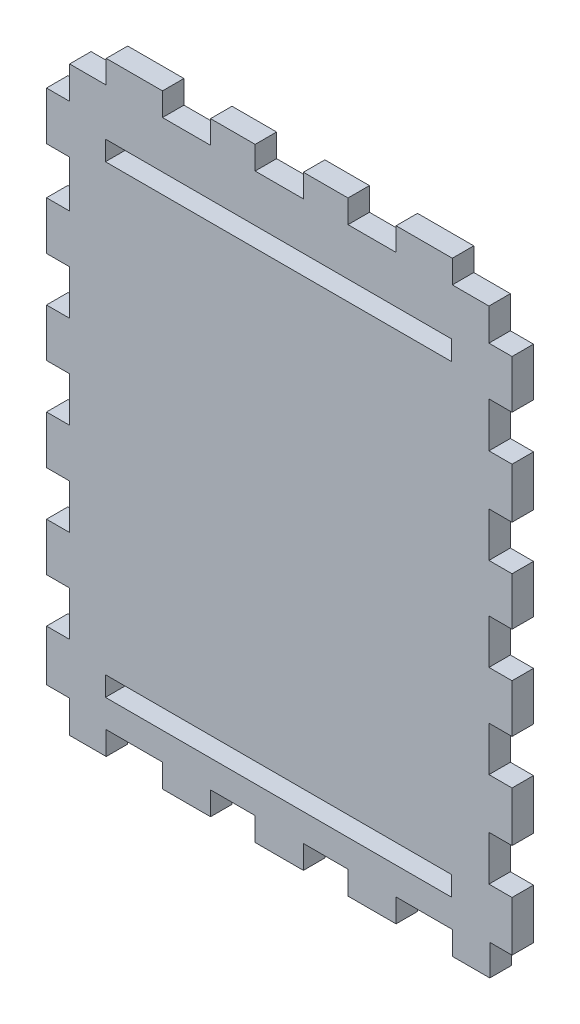
SolidWorks part; units mm, degrees
ref_plane "Front Plane" through (0, 0, 0) normal (0, 0, 1) x (1, 0, 0)
ref_plane "Top Plane" through (0, 0, 0) normal (0, 1, 0) x (1, 0, 0)
ref_plane "Right Plane" through (0, 0, 0) normal (1, 0, 0) x (0, 0, -1)
sketch "Model" plane through (0, 0, 0) normal (0, 0, 1) x (1, 0, 0)
  line L0 (167.6676, 180.7633) -> (171.654, 180.7633)
  line L1 (171.654, 180.7633) -> (171.654, 172.0927)
  line L2 (171.654, 172.0927) -> (167.6676, 172.0927)
  line L3 (167.6676, 172.0927) -> (167.6676, 164.4022)
  line L4 (167.6676, 164.4022) -> (171.654, 164.4022)
  line L5 (171.654, 164.4022) -> (171.654, 156.1119)
  line L6 (171.654, 156.1119) -> (167.6676, 156.1119)
  line L7 (167.6676, 156.1119) -> (167.6676, 153.3045)
  line L8 (95.3481, 202.3963) -> (101.6629, 202.3963)
  line L9 (101.6629, 202.3963) -> (101.6629, 206.3827)
  line L10 (101.6629, 206.3827) -> (111.3643, 206.3827)
  line L11 (111.3643, 206.3827) -> (111.3643, 202.3963)
  line L12 (111.3643, 202.3963) -> (119.6545, 202.3963)
  line L13 (119.6545, 202.3963) -> (119.6545, 206.3827)
  line L14 (119.6545, 206.3827) -> (127.3451, 206.3827)
  line L15 (127.3451, 206.3827) -> (127.3451, 202.3963)
  line L16 (127.3451, 202.3963) -> (135.6706, 202.3963)
  line L17 (135.6706, 202.3963) -> (135.6706, 206.3827)
  line L18 (135.6706, 206.3827) -> (143.3612, 206.3827)
  line L19 (143.3612, 206.3827) -> (143.3612, 202.3963)
  line L20 (143.3612, 202.3963) -> (151.6515, 202.3963)
  line L21 (151.6515, 202.3963) -> (151.6515, 206.3827)
  line L22 (151.6515, 206.3827) -> (161.3529, 206.3827)
  line L23 (161.3529, 206.3827) -> (161.3529, 202.3963)
  line L24 (161.3529, 202.3963) -> (167.6676, 202.3963)
  line L25 (95.3481, 124.1149) -> (91.3617, 124.1149)
  line L26 (91.3617, 124.1149) -> (91.3617, 132.4052)
  line L27 (91.3617, 132.4052) -> (95.3481, 132.4052)
  line L28 (95.3481, 132.4052) -> (95.3481, 140.0958)
  line L29 (95.3481, 140.0958) -> (91.3617, 140.0958)
  line L30 (91.3617, 140.0958) -> (91.3617, 148.4213)
  line L31 (91.3617, 148.4213) -> (95.3481, 148.4213)
  line L32 (95.3481, 148.4213) -> (95.3481, 156.1119)
  line L33 (95.3481, 156.1119) -> (91.3617, 156.1119)
  line L34 (91.3617, 156.1119) -> (91.3617, 164.4022)
  line L35 (91.3617, 164.4022) -> (95.3481, 164.4022)
  line L36 (95.3481, 164.4022) -> (95.3481, 172.0927)
  line L37 (95.3481, 172.0927) -> (91.3617, 172.0927)
  line L38 (91.3617, 172.0927) -> (91.3617, 180.4183)
  line L39 (91.3617, 180.4183) -> (95.3481, 180.4183)
  line L40 (95.3481, 102.1016) -> (101.6628, 102.1016)
  line L41 (101.6628, 102.1016) -> (101.6628, 106.1233)
  line L42 (101.6628, 106.1233) -> (111.3642, 106.1233)
  line L43 (111.3642, 106.1233) -> (111.3642, 102.1016)
  line L44 (111.3642, 102.1016) -> (119.6545, 102.1016)
  line L45 (119.6545, 102.1016) -> (119.6545, 106.1233)
  line L46 (119.6545, 106.1233) -> (127.3451, 106.1233)
  line L47 (127.3451, 106.1233) -> (127.3451, 102.1016)
  line L48 (127.3451, 102.1016) -> (135.6706, 102.1016)
  line L49 (135.6706, 102.1016) -> (135.6706, 106.1233)
  line L50 (135.6706, 106.1233) -> (143.3612, 106.1233)
  line L51 (143.3612, 106.1233) -> (143.3612, 102.1016)
  line L52 (143.3612, 102.1016) -> (151.6515, 102.1016)
  line L53 (151.6515, 102.1016) -> (151.6515, 106.1233)
  line L54 (151.6515, 106.1233) -> (161.3528, 106.1233)
  line L55 (161.3528, 106.1233) -> (161.3528, 102.1016)
  line L56 (161.3528, 102.1016) -> (167.8204, 102.1037)
  line L57 (167.6676, 136.4004) -> (167.6676, 132.4052)
  line L58 (167.6676, 132.4052) -> (171.654, 132.4052)
  line L59 (171.654, 132.4052) -> (171.654, 123.7897)
  line L60 (171.654, 123.7897) -> (167.6676, 123.7897)
  line L61 (167.6676, 153.3045) -> (167.6676, 148.4213)
  line L62 (167.6676, 148.4213) -> (171.654, 148.4213)
  line L63 (171.654, 148.4213) -> (171.654, 140.0958)
  line L64 (171.654, 140.0958) -> (167.6676, 140.0958)
  line L65 (167.6676, 140.0958) -> (167.6676, 136.4004)
  line L66 (101.5217, 194.2608) -> (161.2117, 194.2608)
  line L67 (161.2117, 194.2608) -> (161.2117, 190.8741)
  line L68 (161.2117, 190.8741) -> (101.5217, 190.8741)
  line L69 (101.5217, 190.8741) -> (101.5217, 194.2608)
  line L70 (101.5217, 114.2588) -> (161.2117, 114.2588)
  line L71 (161.2117, 114.2588) -> (161.2117, 110.8722)
  line L72 (161.2117, 110.8722) -> (101.5217, 110.8722)
  line L73 (101.5217, 110.8722) -> (101.5217, 114.2588)
  line L74 (167.6676, 124.1149) -> (167.6676, 116.0498)
  line L75 (167.6676, 116.0498) -> (171.654, 116.0498)
  line L76 (171.654, 116.0498) -> (171.654, 107.4297)
  line L77 (171.654, 107.4297) -> (167.6676, 107.4297)
  line L78 (167.8204, 107.4297) -> (167.8204, 102.1037)
  line L79 (167.6676, 188.5822) -> (167.6676, 180.7633)
  line L80 (167.6676, 202.3963) -> (167.6676, 196.8491)
  line L81 (167.6676, 196.8491) -> (171.654, 196.8491)
  line L82 (171.654, 196.8491) -> (171.654, 188.5235)
  line L83 (171.654, 188.5235) -> (167.6676, 188.5235)
  line L84 (95.3481, 107.6671) -> (91.3617, 107.6671)
  line L85 (91.3617, 107.6671) -> (91.3617, 116.4402)
  line L86 (91.3617, 116.4402) -> (95.3481, 116.4402)
  line L87 (95.3481, 116.4402) -> (95.3481, 124.1149)
  line L88 (95.3481, 107.7242) -> (95.3481, 102.1016)
  line L89 (95.3481, 188.4835) -> (91.3617, 188.4835)
  line L90 (91.3617, 188.4835) -> (91.3617, 196.809)
  line L91 (91.3617, 196.809) -> (95.3481, 196.809)
  line L92 (95.3481, 196.809) -> (95.3481, 202.3963)
  line L93 (95.3481, 180.4183) -> (95.3481, 188.4835)
extrude "Boss-Extrude1" add sketch "Model" along normal blind 3.7
